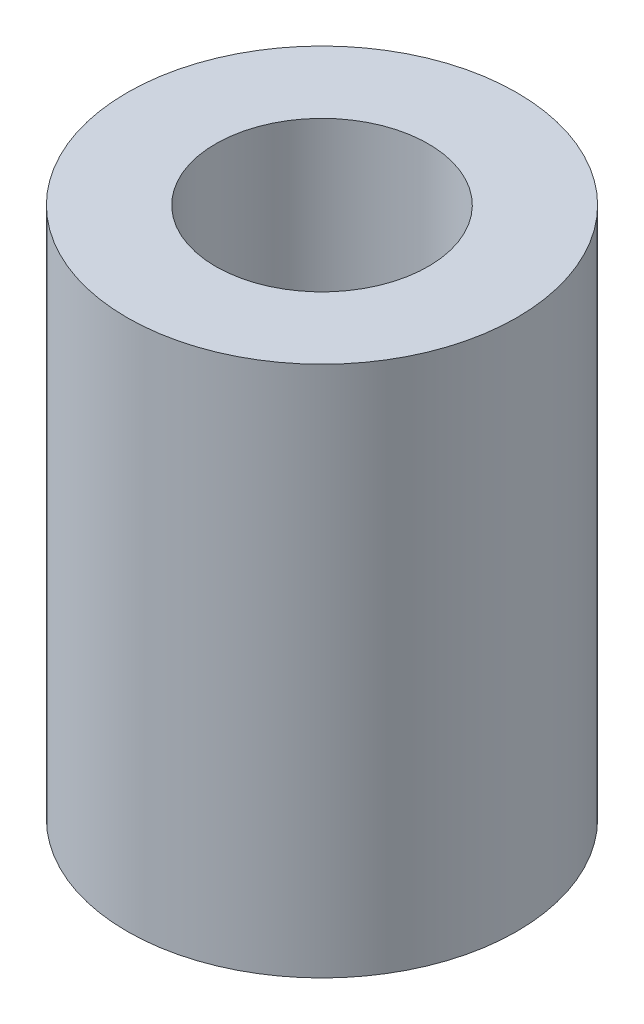
SolidWorks part; units mm, degrees
ref_plane "前视基准面" through (0, 0, 0) normal (0, 0, 1) x (1, 0, 0)
ref_plane "上视基准面" through (0, 0, 0) normal (0, 1, 0) x (1, 0, 0)
ref_plane "右视基准面" through (0, 0, 0) normal (1, 0, 0) x (0, 0, -1)
sketch "草图1" plane through (0, 0, 0) normal (0, 1, 0) x (1, 0, 0)
  circle A0 centre (0, 0) radius 6
  circle A1 centre (0, 0) radius 11
  dimension "D1" = 12
  dimension "D2" = 22
extrude "凸台-拉伸1" add sketch "草图1" along normal blind 30
sketch "草图2" plane through (0, 0, 0) normal (1, 0, 0) x (0, 0, -1)
  line L0 (-11, 0) -> (11, 22)
  line L1 (11, 0) -> (11, 30) construction
  line L2 (-11, 0) -> (11, 0) construction
  line L3 (-11, 0) -> (11, 0)
  line L4 (11, 22) -> (11, 0)
  dimension "D1" = 45
